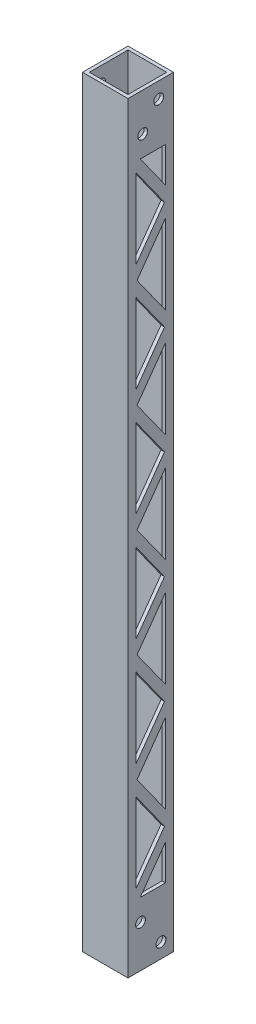
SolidWorks part; units mm, degrees
material "5052-H32"
ref_plane "Front Plane" through (0, 0, 0) normal (0, 0, 1) x (1, 0, 0)
ref_plane "Top Plane" through (0, 0, 0) normal (0, 1, 0) x (1, 0, 0)
ref_plane "Right Plane" through (0, 0, 0) normal (1, 0, 0) x (0, 0, -1)
sketch "Sketch2" plane through (0, 0, 0) normal (0, 1, 0) x (1, 0, 0)
  line L0 (-10, 10) -> (10, 10) construction
  line L1 (8.5, -8.5) -> (-8.5, -8.5)
  line L2 (8.5, -8.5) -> (8.5, 8.5)
  line L3 (8.5, 8.5) -> (-8.5, 8.5)
  line L4 (-8.5, -8.5) -> (-8.5, 8.5)
  line L5 (8.5, -8.5) -> (-8.5, 8.5) construction
  line L6 (8.5, 8.5) -> (-8.5, -8.5) construction
  line L7 (10, -10) -> (-10, -10)
  line L8 (10, -10) -> (10, 10)
  line L9 (10, 10) -> (-10, 10)
  line L10 (-10, -10) -> (-10, 10)
  line L11 (10, -10) -> (-10, 10) construction
  line L12 (10, 10) -> (-10, -10) construction
  point P0 (0, 0)
  point P7 (0, 0)
extrude "Boss-Extrude1" add sketch "Sketch2" against normal up to vertex (323.2202 mm away) from vertex at 11.8734
hole_wizard "M4 Clearance Hole1" positions "Sketch3" profile "Sketch5" hole size "M4" standard "ISO" end condition up to next
sketch "Sketch3" plane through (-10, 0, 0) normal (-1, 0, 0) x (0, 0, 1)
  point P0 (3.5, 4.8734)
  point P2 (-3.5, -4.8734)
sketch "Sketch5" plane through (-10, 4.8734, 3.5) normal (0, 1, 0) x (0, 0, 1)
  line L0 (0, 0) -> (0, 1.5)
  line L1 (0, 1.5) -> (2.15, 1.5)
  line L2 (2.15, 1.5) -> (2.15, 0.025)
  line L3 (2.15, 0.025) -> (2.175, 0)
  line L5 (2.175, 0) -> (0, 0)
  line L6 (-2.15, 0.025) -> (-2.175, 0) construction
  line L11 (0, -6.35) -> (0, 107.95) construction
  dimension "Thru Hole Dia." = 4.3
  dimension "Thru Hole Depth" = 1.5
  dimension "Near C'Sink Dia." = 4.35
  dimension "Near C'Sink Angle" = 90
hole_wizard "M4 Clearance Hole2" positions "Sketch6" profile "Sketch8" hole size "M4" standard "ISO" end condition up to next
sketch "Sketch6" plane through (10, 0, 0) normal (1, 0, 0) x (0, 0, -1)
  point P0 (3.5, 4.8734)
  point P2 (-3.5, -4.8734)
sketch "Sketch8" plane through (10, 4.8734, -3.5) normal (0, 1, 0) x (0, 0, -1)
  line L0 (0, 0) -> (0, 1.5)
  line L1 (0, 1.5) -> (2.15, 1.5)
  line L2 (2.15, 1.5) -> (2.15, 0.025)
  line L3 (2.15, 0.025) -> (2.175, 0)
  line L5 (2.175, 0) -> (0, 0)
  line L6 (-2.15, 0.025) -> (-2.175, 0) construction
  line L11 (0, -6.35) -> (0, 107.95) construction
  dimension "Thru Hole Dia." = 4.3
  dimension "Thru Hole Depth" = 1.5
  dimension "Near C'Sink Dia." = 4.35
  dimension "Near C'Sink Angle" = 90
hole_wizard "M4 Clearance Hole3" positions "Sketch9" profile "Sketch10" hole size "M4" standard "ISO" end condition up to next
sketch "Sketch9" plane through (-10, 0, 0) normal (-1, 0, 0) x (0, 0, 1)
  point P0 (-4.5, -304.7202)
  point P2 (4.5, -316.7202)
sketch "Sketch10" plane through (-10, -304.7202, -4.5) normal (0, 1, 0) x (0, 0, 1)
  line L0 (0, 0) -> (0, 1.5)
  line L1 (0, 1.5) -> (2.15, 1.5)
  line L2 (2.15, 1.5) -> (2.15, 0.025)
  line L3 (2.15, 0.025) -> (2.175, 0)
  line L5 (2.175, 0) -> (0, 0)
  line L6 (-2.15, 0.025) -> (-2.175, 0) construction
  line L11 (0, -6.35) -> (0, 107.95) construction
  dimension "Thru Hole Dia." = 4.3
  dimension "Thru Hole Depth" = 1.5
  dimension "Near C'Sink Dia." = 4.35
  dimension "Near C'Sink Angle" = 90
hole_wizard "M4 Clearance Hole4" positions "Sketch11" profile "Sketch12" hole size "M4" standard "ISO" end condition up to next
sketch "Sketch11" plane through (10, 0, 0) normal (1, 0, 0) x (0, 0, -1)
  point P0 (-4.5, -304.7202)
  point P2 (4.5, -316.7202)
sketch "Sketch12" plane through (10, -304.7202, 4.5) normal (0, 1, 0) x (0, 0, -1)
  line L0 (0, 0) -> (0, 1.5)
  line L1 (0, 1.5) -> (2.15, 1.5)
  line L2 (2.15, 1.5) -> (2.15, 0.025)
  line L3 (2.15, 0.025) -> (2.175, 0)
  line L5 (2.175, 0) -> (0, 0)
  line L6 (-2.15, 0.025) -> (-2.175, 0) construction
  line L11 (0, -6.35) -> (0, 107.95) construction
  dimension "Thru Hole Dia." = 4.3
  dimension "Thru Hole Depth" = 1.5
  dimension "Near C'Sink Dia." = 4.35
  dimension "Near C'Sink Angle" = 90
sketch "Sketch13" plane through (0, 0, 0) normal (1, 0, 0) x (0, 0, -1)
  line L0 (6.5, -279.6777) -> (-4.6116, -295.2202) construction
  line L1 (-4.6116, -295.2202) -> (6.5, -295.2202) construction
  line L2 (6.5, -279.6777) -> (6.5, -295.2202) construction
  line L3 (-6.5, -255.8988) -> (6.0415, -273.4413) construction
  line L4 (6.0415, -273.4413) -> (-6.5, -290.9838) construction
  line L5 (-6.5, -255.8988) -> (-6.5, -290.9838) construction
  line L6 (6.5, -232.1199) -> (-6.0415, -249.6624) construction
  line L7 (-6.0415, -249.6624) -> (6.5, -267.2049) construction
  line L8 (6.5, -232.1199) -> (6.5, -267.2049) construction
  line L9 (-6.5, -208.341) -> (6.0415, -225.8835) construction
  line L10 (6.0415, -225.8835) -> (-6.5, -243.426) construction
  line L11 (-6.5, -208.341) -> (-6.5, -243.426) construction
  line L12 (6.5, -184.5621) -> (-6.0415, -202.1046) construction
  line L13 (-6.0415, -202.1046) -> (6.5, -219.6471) construction
  line L14 (6.5, -184.5621) -> (6.5, -219.6471) construction
  line L15 (-6.5, -160.7832) -> (6.0415, -178.3257) construction
  line L16 (6.0415, -178.3257) -> (-6.5, -195.8682) construction
  line L17 (-6.5, -160.7832) -> (-6.5, -195.8682) construction
  line L18 (6.5, -137.0043) -> (-6.0415, -154.5468) construction
  line L19 (-6.0415, -154.5468) -> (6.5, -172.0893) construction
  line L20 (6.5, -137.0043) -> (6.5, -172.0893) construction
  line L21 (-6.5, -113.2254) -> (6.0415, -130.7679) construction
  line L22 (6.0415, -130.7679) -> (-6.5, -148.3104) construction
  line L23 (-6.5, -113.2254) -> (-6.5, -148.3104) construction
  line L24 (6.5, -89.4465) -> (-6.0415, -106.989) construction
  line L25 (-6.0415, -106.989) -> (6.5, -124.5315) construction
  line L26 (6.5, -89.4465) -> (6.5, -124.5315) construction
  line L27 (-6.5, -65.6676) -> (6.0415, -83.2101) construction
  line L28 (6.0415, -83.2101) -> (-6.5, -100.7526) construction
  line L29 (-6.5, -65.6676) -> (-6.5, -100.7526) construction
  line L30 (-6.0415, -59.4312) -> (6.5, -76.9737) construction
  line L31 (6.5, -41.8887) -> (6.5, -76.9737) construction
  line L32 (6.5, -41.8887) -> (-6.0415, -59.4312) construction
  line L33 (-6.5, -18.1098) -> (6.0415, -35.6523) construction
  line L34 (6.0415, -35.6523) -> (-6.5, -53.1948) construction
  line L35 (-6.5, -53.1948) -> (-6.5, -18.1098) construction
  line L36 (6.5, -13.8734) -> (6.5, -29.4159) construction
  line L37 (-4.6116, -13.8734) -> (6.5, -29.4159) construction
  line L38 (6.5, -13.8734) -> (-4.6116, -13.8734) construction
  line L39 (6.5, -279.6777) -> (-4.6116, -295.2202)
  line L40 (-4.6116, -295.2202) -> (6.5, -295.2202)
  line L41 (6.5, -279.6777) -> (6.5, -295.2202)
  line L42 (-6.5, -255.8988) -> (6.0415, -273.4413)
  line L43 (6.0415, -273.4413) -> (-6.5, -290.9838)
  line L44 (-6.5, -255.8988) -> (-6.5, -290.9838)
  line L45 (6.5, -232.1199) -> (-6.0415, -249.6624)
  line L46 (-6.0415, -249.6624) -> (6.5, -267.2049)
  line L47 (6.5, -232.1199) -> (6.5, -267.2049)
  line L48 (-6.5, -208.341) -> (6.0415, -225.8835)
  line L49 (6.0415, -225.8835) -> (-6.5, -243.426)
  line L50 (-6.5, -208.341) -> (-6.5, -243.426)
  line L51 (6.5, -184.5621) -> (-6.0415, -202.1046)
  line L52 (-6.0415, -202.1046) -> (6.5, -219.6471)
  line L53 (6.5, -184.5621) -> (6.5, -219.6471)
  line L54 (-6.5, -160.7832) -> (6.0415, -178.3257)
  line L55 (6.0415, -178.3257) -> (-6.5, -195.8682)
  line L56 (-6.5, -160.7832) -> (-6.5, -195.8682)
  line L57 (6.5, -137.0043) -> (-6.0415, -154.5468)
  line L58 (-6.0415, -154.5468) -> (6.5, -172.0893)
  line L59 (6.5, -137.0043) -> (6.5, -172.0893)
  line L60 (-6.5, -113.2254) -> (6.0415, -130.7679)
  line L61 (6.0415, -130.7679) -> (-6.5, -148.3104)
  line L62 (-6.5, -113.2254) -> (-6.5, -148.3104)
  line L63 (6.5, -89.4465) -> (-6.0415, -106.989)
  line L64 (-6.0415, -106.989) -> (6.5, -124.5315)
  line L65 (6.5, -89.4465) -> (6.5, -124.5315)
  line L66 (-6.5, -65.6676) -> (6.0415, -83.2101)
  line L67 (6.0415, -83.2101) -> (-6.5, -100.7526)
  line L68 (-6.5, -65.6676) -> (-6.5, -100.7526)
  line L69 (-6.0415, -59.4312) -> (6.5, -76.9737)
  line L70 (6.5, -41.8887) -> (6.5, -76.9737)
  line L71 (6.5, -41.8887) -> (-6.0415, -59.4312)
  line L72 (-6.5, -18.1098) -> (6.0415, -35.6523)
  line L73 (6.0415, -35.6523) -> (-6.5, -53.1948)
  line L74 (-6.5, -53.1948) -> (-6.5, -18.1098)
  line L75 (6.5, -13.8734) -> (6.5, -29.4159)
  line L76 (-4.6116, -13.8734) -> (6.5, -29.4159)
  line L77 (6.5, -13.8734) -> (-4.6116, -13.8734)
extrude "Cut-Extrude1" cut sketch "Sketch13" against normal through all and the other way through all
